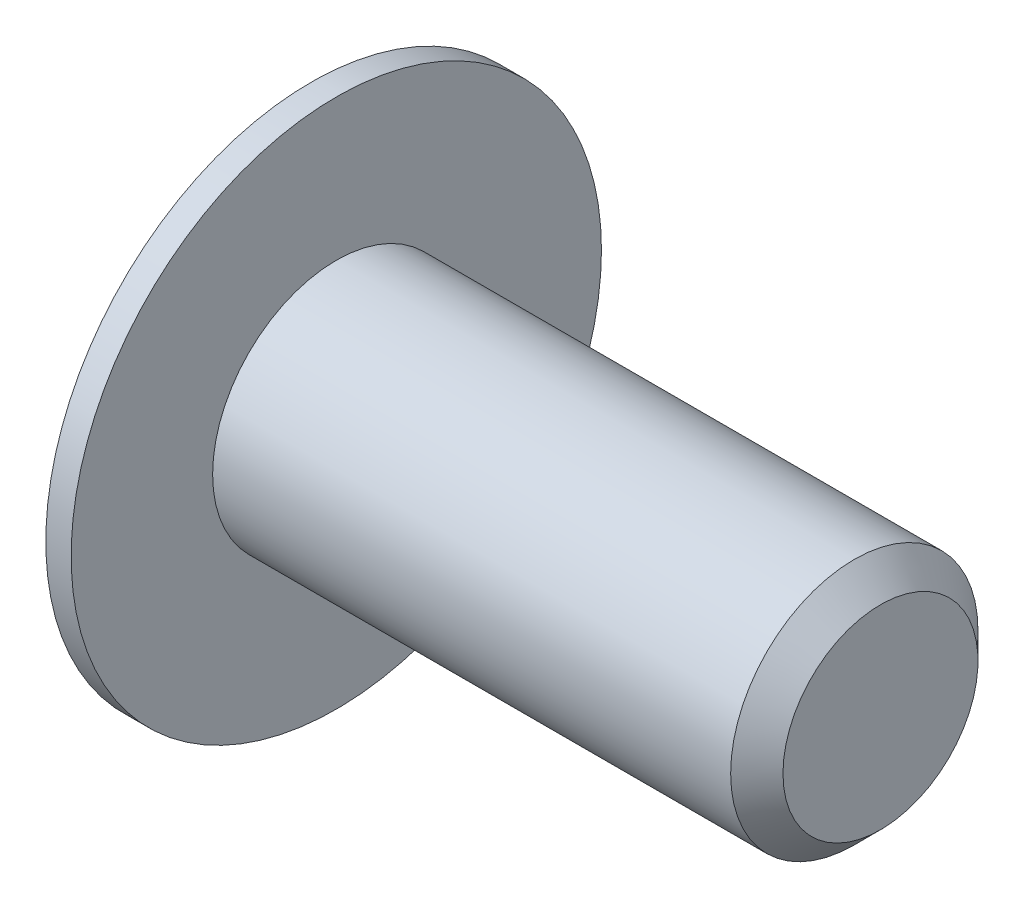
SolidWorks part; units mm, degrees
ref_plane "Front Plane" through (0, 0, 0) normal (0, 0, 1) x (1, 0, 0)
ref_plane "Top Plane" through (0, 0, 0) normal (0, 1, 0) x (1, 0, 0)
ref_plane "Right Plane" through (0, 0, 0) normal (1, 0, 0) x (0, 0, -1)
sketch "Sketch1" plane through (0, 0, 0) normal (0, 0, 1) x (1, 0, 0)
  line L0 (-4.064, 2.8956) -> (-4.064, 0)
  line L1 (-4.064, 0) -> (0, 0)
  line L2 (0, 0) -> (0, 8.509)
  line L3 (0, 8.509) -> (-0.8128, 8.509)
  line L4 (-0.8128, 8.509) -> (-0.8128, 7.6581)
  line L5 (-4.064, 0) -> (0, 0) construction
  arc A0 (-0.8128, 7.6581) -> (-4.064, 2.8956) centre (4.1735, 0.7632) ccw
revolve "Revolve1" add sketch "Sketch1" angle 360 about L5
sketch "Sketch2" plane through (0, 0, 0) normal (1, 0, 0) x (0, 0, -1)
  circle A0 centre (0, 0) radius 3.9688
extrude "Boss-Extrude1" add sketch "Sketch2" along normal blind 17.4625
sketch "Sketch3" plane through (-4.064, 0, 0) normal (-1, 0, 0) x (0, 0, 1)
  line L0 (0, -2.7863) -> (2.413, -1.3931)
  line L1 (2.413, -1.3931) -> (2.413, 1.3931)
  line L2 (2.413, 1.3931) -> (0, 2.7863)
  line L3 (0, 2.7863) -> (-2.413, 1.3931)
  line L4 (-2.413, 1.3931) -> (-2.413, -1.3931)
  line L5 (-2.413, -1.3931) -> (0, -2.7863)
extrude "Cut-Extrude1" cut sketch "Sketch3" against normal blind 3.556
chamfer "Chamfer1" distance 0.8395 angle 45 1 edges at (17.4625, 0, -3.9688)
